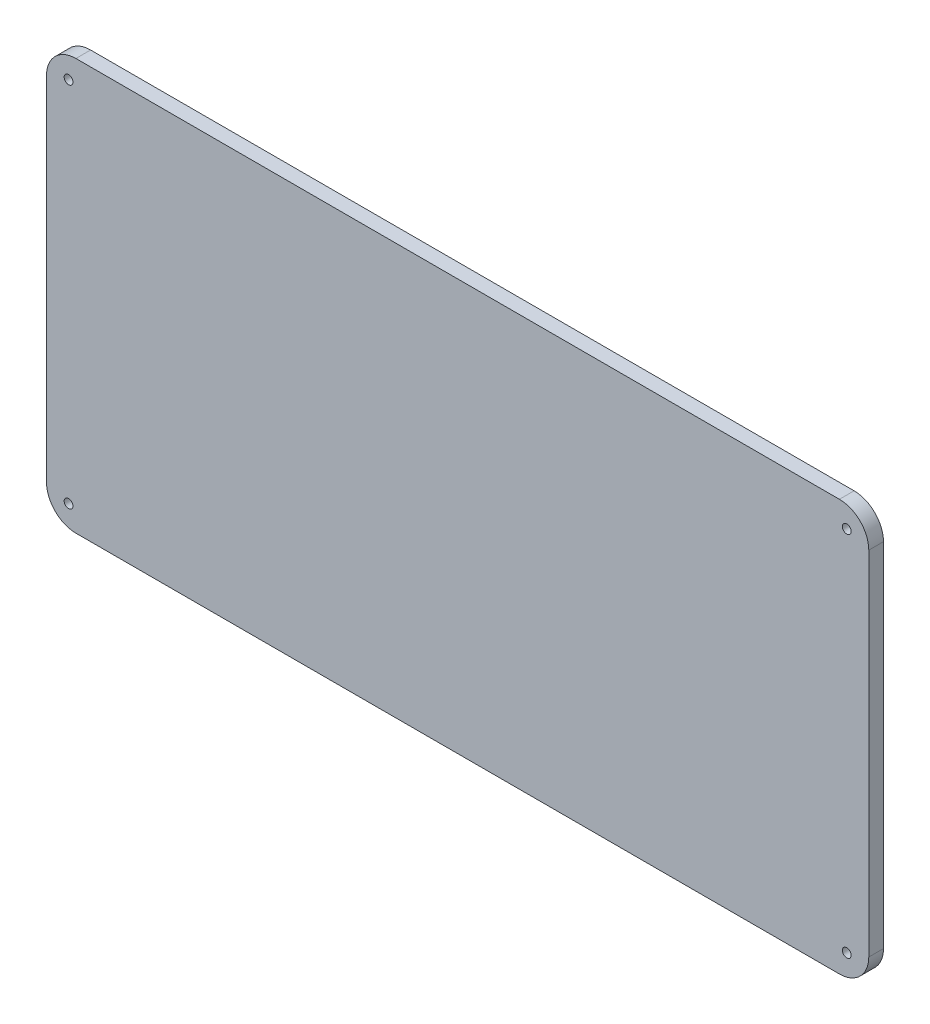
SolidWorks part; units mm, degrees
ref_plane "Front Plane" through (0, 0, 0) normal (0, 0, 1) x (1, 0, 0)
ref_plane "Top Plane" through (0, 0, 0) normal (0, 1, 0) x (1, 0, 0)
ref_plane "Right Plane" through (0, 0, 0) normal (1, 0, 0) x (0, 0, -1)
sketch "Sketch1" plane through (0, 0, 0) normal (0, 0, 1) x (1, 0, 0)
  line L0 (130, -70) -> (-130, -70) construction
  line L1 (130, -70) -> (-130, -70)
  line L2 (-140, 60) -> (-140, -60) construction
  line L3 (130, 70) -> (-130, 70) construction
  line L4 (140, 60) -> (140, -60) construction
  line L5 (-140, 60) -> (-140, -60)
  line L6 (130, 70) -> (-130, 70)
  line L7 (140, 60) -> (140, -60)
  line L12 (130, 62) -> (130, 63)
  line L13 (133, 60) -> (132, 60)
  line L14 (135, -58) -> (135, 58)
  line L15 (132, -60) -> (133, -60)
  line L16 (130, -63) -> (130, -62)
  line L17 (-128, -65) -> (128, -65)
  line L18 (-130, -62) -> (-130, -63)
  line L19 (-133, -60) -> (-132, -60)
  line L20 (-135, 58) -> (-135, -58)
  line L21 (-132, 60) -> (-133, 60)
  line L22 (-130, 63) -> (-130, 62)
  line L23 (128, 65) -> (-128, 65)
  line L24 (130, 62) -> (130, 63)
  line L25 (133, 60) -> (132, 60)
  line L26 (135, -58) -> (135, 58)
  line L27 (132, -60) -> (133, -60)
  line L28 (130, -63) -> (130, -62)
  line L29 (-128, -65) -> (128, -65)
  line L30 (-130, -62) -> (-130, -63)
  line L31 (-133, -60) -> (-132, -60)
  line L32 (-135, 58) -> (-135, -58)
  line L33 (-132, 60) -> (-133, 60)
  line L34 (-130, 63) -> (-130, 62)
  line L35 (128, 65) -> (-128, 65)
  arc A0 (-140, -60) -> (-130, -70) centre (-130, -60) ccw construction
  arc A1 (-140, -60) -> (-130, -70) centre (-130, -60) ccw
  arc A2 (-130, 70) -> (-140, 60) centre (-130, 60) ccw construction
  arc A3 (140, 60) -> (130, 70) centre (130, 60) ccw construction
  arc A4 (130, -70) -> (140, -60) centre (130, -60) ccw construction
  arc A5 (-130, 70) -> (-140, 60) centre (-130, 60) ccw
  arc A6 (140, 60) -> (130, 70) centre (130, 60) ccw
  arc A7 (130, -70) -> (140, -60) centre (130, -60) ccw
  circle A9 centre (132.5, 62.5) radius 1.5
  circle A10 centre (132.5, 62.5) radius 1.5
  circle A11 centre (-132.5, 62.5) radius 1.5
  arc A12 (130, 62) -> (132, 60) centre (132, 62) ccw
  arc A13 (135, 58) -> (133, 60) centre (133, 58) ccw
  arc A14 (133, -60) -> (135, -58) centre (133, -58) ccw
  arc A15 (132, -60) -> (130, -62) centre (132, -62) ccw
  arc A16 (128, -65) -> (130, -63) centre (128, -63) ccw
  arc A17 (-130, -63) -> (-128, -65) centre (-128, -63) ccw
  arc A18 (-130, -62) -> (-132, -60) centre (-132, -62) ccw
  arc A19 (-135, -58) -> (-133, -60) centre (-133, -58) ccw
  arc A20 (-133, 60) -> (-135, 58) centre (-133, 58) ccw
  arc A21 (-132, 60) -> (-130, 62) centre (-132, 62) ccw
  arc A22 (-128, 65) -> (-130, 63) centre (-128, 63) ccw
  arc A23 (130, 63) -> (128, 65) centre (128, 63) ccw
  arc A24 (130, 62) -> (132, 60) centre (132, 62) ccw
  arc A25 (135, 58) -> (133, 60) centre (133, 58) ccw
  arc A26 (133, -60) -> (135, -58) centre (133, -58) ccw
  arc A27 (132, -60) -> (130, -62) centre (132, -62) ccw
  arc A28 (128, -65) -> (130, -63) centre (128, -63) ccw
  arc A29 (-130, -63) -> (-128, -65) centre (-128, -63) ccw
  arc A30 (-130, -62) -> (-132, -60) centre (-132, -62) ccw
  arc A31 (-135, -58) -> (-133, -60) centre (-133, -58) ccw
  arc A32 (-133, 60) -> (-135, 58) centre (-133, 58) ccw
  arc A33 (-132, 60) -> (-130, 62) centre (-132, 62) ccw
  arc A34 (-128, 65) -> (-130, 63) centre (-128, 63) ccw
  arc A35 (130, 63) -> (128, 65) centre (128, 63) ccw
  circle A36 centre (-132.5, 62.5) radius 1.5
  circle A37 centre (-132.5, -62.5) radius 1.5
  circle A38 centre (-132.5, -62.5) radius 1.5
  circle A39 centre (132.5, -62.5) radius 1.5
  circle A40 centre (132.5, -62.5) radius 1.5
  dimension "D1" = 0
  dimension "D2" = 0
  dimension "D3" = 0
  dimension "D4" = 0
  dimension "D5" = 0
extrude "Boss-Extrude2" add sketch "Sketch1" along normal blind 3
sketch "Sketch2" plane through (0, 0, 3) normal (0, 0, 1) x (1, 0, 0)
  line L4 (-130, -70) -> (130, -70)
  line L5 (140, -60) -> (140, 60)
  line L6 (130, 70) -> (-130, 70)
  line L7 (-140, 60) -> (-140, -60)
  line L8 (-130, -70) -> (130, -70)
  line L9 (140, -60) -> (140, 60)
  line L10 (130, 70) -> (-130, 70)
  line L11 (-140, 60) -> (-140, -60)
  arc A4 (-140, -60) -> (-130, -70) centre (-130, -60) ccw
  arc A5 (130, -70) -> (140, -60) centre (130, -60) ccw
  arc A6 (140, 60) -> (130, 70) centre (130, 60) ccw
  arc A7 (-130, 70) -> (-140, 60) centre (-130, 60) ccw
  arc A8 (-140, -60) -> (-130, -70) centre (-130, -60) ccw
  arc A9 (130, -70) -> (140, -60) centre (130, -60) ccw
  arc A10 (140, 60) -> (130, 70) centre (130, 60) ccw
  arc A11 (-130, 70) -> (-140, 60) centre (-130, 60) ccw
  dimension "D1" = 0
extrude "Boss-Extrude3" add sketch "Sketch2" along normal blind 2
sketch "Sketch3" plane through (0, 0, 0) normal (0, 0, -1) x (-1, 0, 0)
  circle A0 centre (132.5, -62.5) radius 1.5 construction
  circle A1 centre (-132.5, -62.5) radius 1.5
  circle A2 centre (-132.5, -62.5) radius 1.5
  circle A3 centre (-132.5, 62.5) radius 1.5
  circle A4 centre (-132.5, 62.5) radius 1.5
  circle A5 centre (132.5, 62.5) radius 1.5 construction
  circle A6 centre (132.5, -62.5) radius 1.5
  circle A7 centre (132.5, 62.5) radius 1.5
  dimension "D1" = 0
  dimension "D2" = 0
extrude "Cut-Extrude1" cut sketch "Sketch3" against normal blind 15.208
sketch "Sketch4" plane through (0, 0, 3) normal (0, 0, -1) x (-1, 0, 0)
  line L0 (128, 64) -> (-128, 64)
  line L1 (-129, 63) -> (-129, 62)
  line L2 (-132, 59) -> (-133, 59)
  line L3 (-134, 58) -> (-134, -58)
  line L4 (-133, -59) -> (-132, -59)
  line L5 (-129, -62) -> (-129, -63)
  line L6 (-128, -64) -> (128, -64)
  line L7 (129, -63) -> (129, -62)
  line L8 (132, -59) -> (133, -59)
  line L9 (134, -58) -> (134, 58)
  line L10 (133, 59) -> (132, 59)
  line L11 (129, 62) -> (129, 63)
  line L12 (-130, 63) -> (-130, 62)
  line L13 (-132, 60) -> (-133, 60)
  line L14 (-135, 58) -> (-135, -58)
  line L15 (-133, -60) -> (-132, -60)
  line L16 (-130, -62) -> (-130, -63)
  line L17 (-128, -65) -> (128, -65)
  line L18 (130, -63) -> (130, -62)
  line L19 (132, -60) -> (133, -60)
  line L20 (135, -58) -> (135, 58)
  line L21 (133, 60) -> (132, 60)
  line L22 (130, 62) -> (130, 63)
  line L23 (128, 65) -> (-128, 65)
  line L34 (130, 62) -> (130, 63)
  line L36 (-135, 58) -> (-135, -58) construction
  line L37 (-133, -60) -> (-132, -60) construction
  line L38 (-130, -62) -> (-130, -63) construction
  line L39 (-128, -65) -> (128, -65) construction
  line L40 (130, -63) -> (130, -62) construction
  line L41 (132, -60) -> (133, -60) construction
  line L42 (135, -58) -> (135, 58) construction
  line L43 (133, 60) -> (132, 60) construction
  line L44 (128, 65) -> (-128, 65) construction
  line L45 (-130, 63) -> (-130, 62) construction
  line L46 (-132, 60) -> (-133, 60) construction
  line L47 (127, 62) -> (-127, 62)
  line L48 (-127, 62) -> (-127, 62)
  line L49 (-132, 57) -> (-132, 57)
  line L50 (-132, 57) -> (-132, -57)
  line L51 (-132, -57) -> (-132, -57)
  line L52 (-127, -62) -> (-127, -62)
  line L53 (-127, -62) -> (127, -62)
  line L54 (127, -62) -> (127, -62)
  line L55 (132, -57) -> (132, -57)
  line L56 (132, -57) -> (132, 57)
  line L57 (132, 57) -> (132, 57)
  line L58 (127, 62) -> (127, 62)
  arc A0 (-128, 64) -> (-129, 63) centre (-128, 63) ccw
  arc A1 (-132, 59) -> (-129, 62) centre (-132, 62) ccw
  arc A2 (-133, 59) -> (-134, 58) centre (-133, 58) ccw
  arc A3 (-134, -58) -> (-133, -59) centre (-133, -58) ccw
  arc A4 (-129, -62) -> (-132, -59) centre (-132, -62) ccw
  arc A5 (-129, -63) -> (-128, -64) centre (-128, -63) ccw
  arc A6 (128, -64) -> (129, -63) centre (128, -63) ccw
  arc A7 (132, -59) -> (129, -62) centre (132, -62) ccw
  arc A8 (133, -59) -> (134, -58) centre (133, -58) ccw
  arc A9 (134, 58) -> (133, 59) centre (133, 58) ccw
  arc A10 (129, 62) -> (132, 59) centre (132, 62) ccw
  arc A11 (129, 63) -> (128, 64) centre (128, 63) ccw
  arc A12 (-128, 65) -> (-130, 63) centre (-128, 63) ccw
  arc A13 (-132, 60) -> (-130, 62) centre (-132, 62) ccw
  arc A14 (-133, 60) -> (-135, 58) centre (-133, 58) ccw
  arc A15 (-135, -58) -> (-133, -60) centre (-133, -58) ccw
  arc A16 (-130, -62) -> (-132, -60) centre (-132, -62) ccw
  arc A17 (-130, -63) -> (-128, -65) centre (-128, -63) ccw
  arc A18 (128, -65) -> (130, -63) centre (128, -63) ccw
  arc A19 (132, -60) -> (130, -62) centre (132, -62) ccw
  arc A20 (133, -60) -> (135, -58) centre (133, -58) ccw
  arc A21 (135, 58) -> (133, 60) centre (133, 58) ccw
  arc A22 (130, 62) -> (132, 60) centre (132, 62) ccw
  arc A23 (130, 63) -> (128, 65) centre (128, 63) ccw
  arc A36 (-135, -58) -> (-133, -60) centre (-133, -58) ccw construction
  arc A37 (-130, -62) -> (-132, -60) centre (-132, -62) ccw construction
  arc A38 (-130, -63) -> (-128, -65) centre (-128, -63) ccw construction
  arc A39 (128, -65) -> (130, -63) centre (128, -63) ccw construction
  arc A40 (132, -60) -> (130, -62) centre (132, -62) ccw construction
  arc A41 (133, -60) -> (135, -58) centre (133, -58) ccw construction
  arc A42 (135, 58) -> (133, 60) centre (133, 58) ccw construction
  arc A43 (130, 62) -> (132, 60) centre (132, 62) ccw construction
  arc A44 (130, 63) -> (128, 65) centre (128, 63) ccw construction
  arc A45 (-128, 65) -> (-130, 63) centre (-128, 63) ccw construction
  arc A46 (-132, 60) -> (-130, 62) centre (-132, 62) ccw construction
  arc A47 (-133, 60) -> (-135, 58) centre (-133, 58) ccw construction
  arc A48 (-127, 62) -> (-127, 62) centre (-127, 62) ccw
  arc A49 (-132, 57) -> (-127, 62) centre (-132, 62) ccw
  arc A50 (-132, 57) -> (-132, 57) centre (-132, 57) ccw
  arc A51 (-132, -57) -> (-132, -57) centre (-132, -57) ccw
  arc A52 (-127, -62) -> (-132, -57) centre (-132, -62) ccw
  arc A53 (-127, -62) -> (-127, -62) centre (-127, -62) ccw
  arc A54 (127, -62) -> (127, -62) centre (127, -62) ccw
  arc A55 (132, -57) -> (127, -62) centre (132, -62) ccw
  arc A56 (132, -57) -> (132, -57) centre (132, -57) ccw
  arc A57 (132, 57) -> (132, 57) centre (132, 57) ccw
  arc A58 (127, 62) -> (132, 57) centre (132, 62) ccw
  arc A59 (127, 62) -> (127, 62) centre (127, 62) ccw
  dimension "D1" = 0
  dimension "D2" = 1
  dimension "D3" = 2
extrude "Boss-Extrude4" add sketch "Sketch4" along normal blind 5 contours L11 A11 L0 A0 L1 A1 L2 A2 L3 A3 L4 A4 L5 A5 L6 A6 L7 A7 L8 A8 L9 A9 L10 A10 L47 A58 L56 A55 L53 A52 L50 A49
